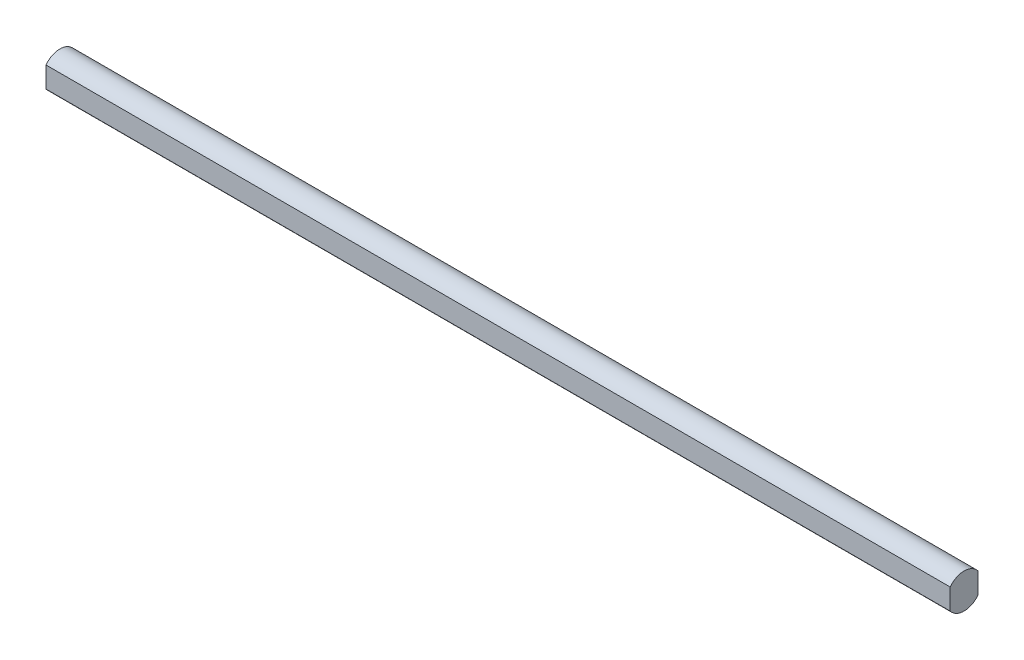
SolidWorks part; units mm, degrees
ref_plane "Plano frontal" through (0, 0, 0) normal (1, 0, 0) x (0, 1, 0)
ref_plane "Plano superior" through (0, 0, 0) normal (0, 0, 1) x (0, 1, 0)
ref_plane "Plano direito" through (0, 0, 0) normal (0, 1, 0) x (-1, 0, 0)
sketch "Esboço1" plane through (0, 0, 0) normal (1, 0, 0) x (0, 1, 0)
  circle A0 centre (0, 0) radius 2.5
  dimension "D1" = 5
extrude "Ressalto-extrusão1" add sketch "Esboço1" along normal mid plane 130
sketch "Esboço2" plane through (65, 0, 0) normal (1, 0, 0) x (0, 1, 0)
  line L1 (-3.1613, 5.466) -> (3.9612, 5.466)
  line L2 (-3.1613, 5.466) -> (-3.1613, 2)
  line L3 (-3.1613, 2) -> (3.9612, 2)
  line L4 (3.9612, 5.466) -> (3.9612, 2)
  dimension "D1" = 2
extrude "Corte-extrusão1" cut sketch "Esboço2" against normal blind 130
mirror "Espelhar1" about plane through (0, 0, 0) normal (0, 0, 1) of "Corte-extrusão1"
